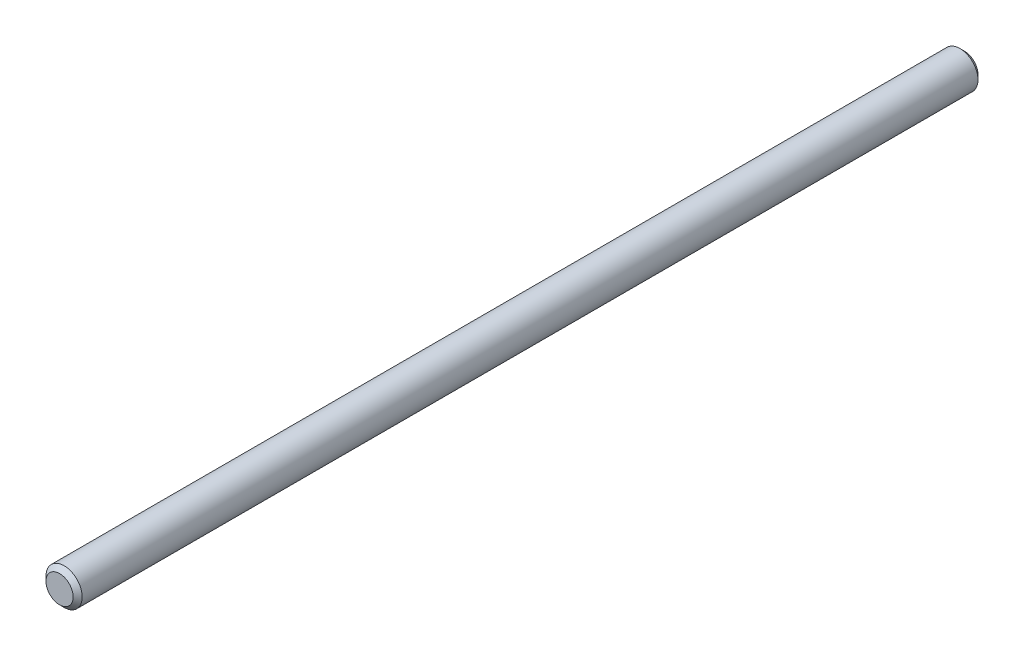
SolidWorks part; units mm, degrees
ref_plane "Alzado" through (0, 0, 0) normal (0, 0, 1) x (1, 0, 0)
ref_plane "Planta" through (0, 0, 0) normal (0, 1, 0) x (1, 0, 0)
ref_plane "Vista lateral" through (0, 0, 0) normal (1, 0, 0) x (0, 0, -1)
sketch "Croquis1" plane through (0, 0, 0) normal (0, 0, 1) x (1, 0, 0)
  circle A0 centre (0, 0) radius 2
extrude "Saliente-Extruir1" add sketch "Croquis1" along normal blind 100
chamfer "Chaflán1" distance 0.5 angle 45 2 edges at (2, 0, 100) (2, 0, 0)
equation "\"D1@Saliente-Extruir1\"= \"Longitud_mm\""
equation "\"D1@Croquis1\"= \"Diametro_mm\""
